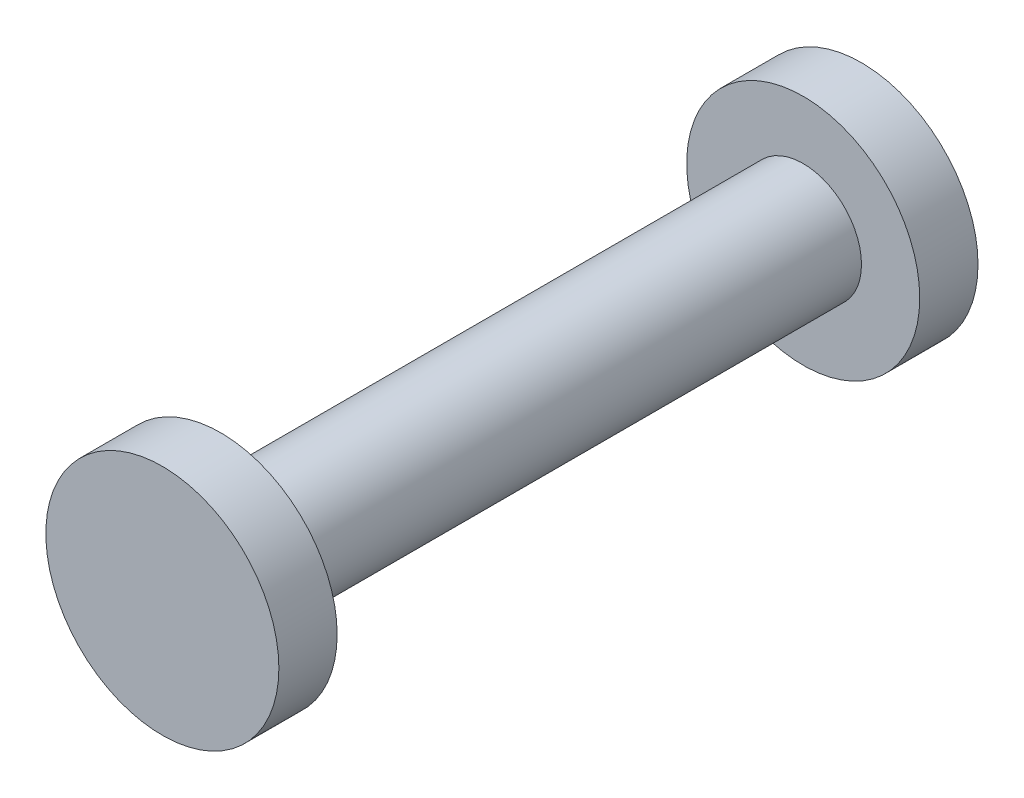
SolidWorks part; units mm, degrees
ref_plane "Front Plane" through (0, 0, 0) normal (0, 0, 1) x (1, 0, 0)
ref_plane "Top Plane" through (0, 0, 0) normal (0, 1, 0) x (1, 0, 0)
ref_plane "Right Plane" through (0, 0, 0) normal (1, 0, 0) x (0, 0, -1)
sketch "Sketch1" plane through (0, 0, 0) normal (0, 0, 1) x (1, 0, 0)
  circle A0 centre (0, 0) radius 5
  dimension "D1" = 10
extrude "Boss-Extrude1" add sketch "Sketch1" along normal mid plane 50
sketch "Sketch2" plane through (0, 0, 25) normal (0, 0, 1) x (1, 0, 0)
  circle A0 centre (0, 0) radius 10
  dimension "D1" = 20
extrude "Boss-Extrude2" add sketch "Sketch2" along normal blind 5
mirror "Mirror2" about plane through (0, 0, 0) normal (0, 0, 1) of "Boss-Extrude2"
